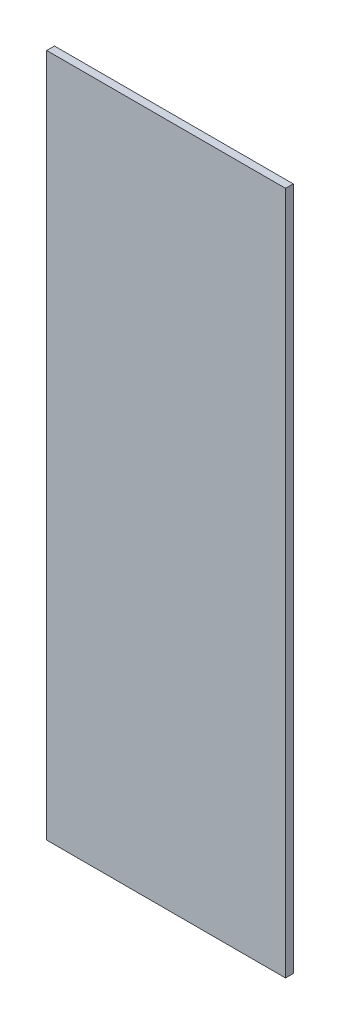
SolidWorks part; units mm, degrees
ref_plane "Front Plane" through (0, 0, 0) normal (0, 0, 1) x (1, 0, 0)
ref_plane "Top Plane" through (0, 0, 0) normal (0, 1, 0) x (1, 0, 0)
ref_plane "Right Plane" through (0, 0, 0) normal (1, 0, 0) x (0, 0, -1)
other "Configuration Table"
sketch "Sketch1" plane through (0, 0, 0) normal (0, 0, 1) x (1, 0, 0)
  line L1 (41.5, 201.5) -> (658.5, 201.5)
  line L2 (41.5, 201.5) -> (41.5, 1968.5)
  line L3 (41.5, 1968.5) -> (658.5, 1968.5)
  line L4 (658.5, 201.5) -> (658.5, 1968.5)
extrude "TOPPING_pu_arka_1" add sketch "Sketch1" against normal blind 20 from offset 798.5 separate body
